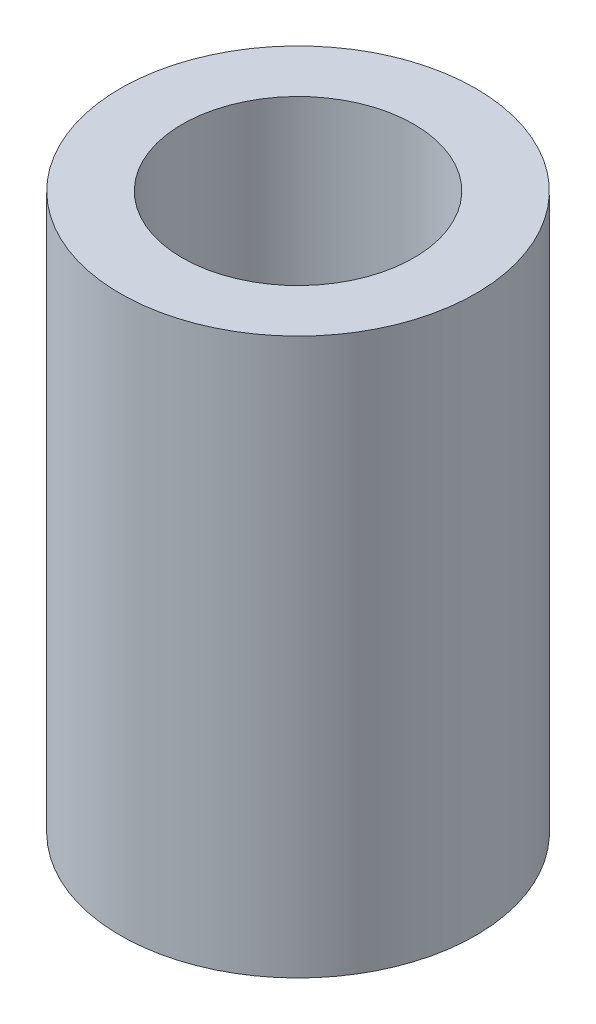
SolidWorks part; units mm, degrees
ref_plane "Front Plane" through (0, 0, 0) normal (0, 0, 1) x (1, 0, 0)
ref_plane "Top Plane" through (0, 0, 0) normal (0, 1, 0) x (1, 0, 0)
ref_plane "Right Plane" through (0, 0, 0) normal (1, 0, 0) x (0, 0, -1)
sketch "Sketch1" plane through (0, 0, 0) normal (0, 1, 0) x (1, 0, 0)
  circle A0 centre (0, 0) radius 1.5875
  circle A1 centre (0, 0) radius 2.4361
  dimension "D1" = 3.175
extrude "Boss-Extrude1" add sketch "Sketch1" along normal blind 7.62
